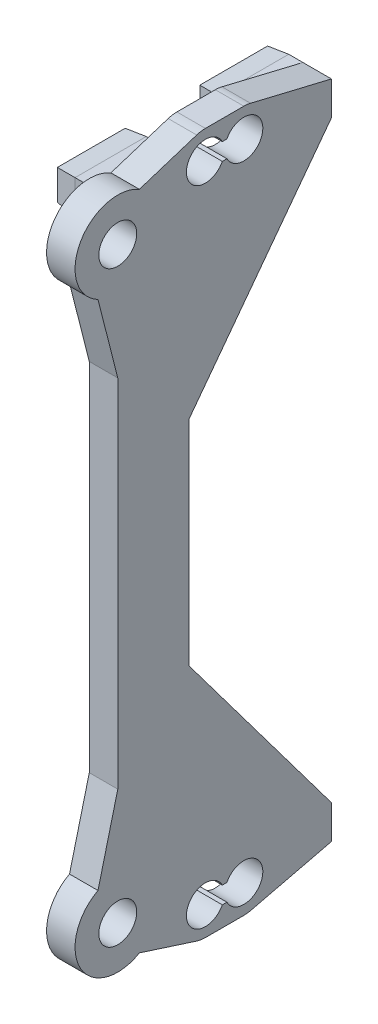
SolidWorks part; units mm, degrees
ref_plane "Front Plane" through (0, 0, 0) normal (0, 0, 1) x (1, 0, 0)
ref_plane "Top Plane" through (0, 0, 0) normal (0, 1, 0) x (1, 0, 0)
ref_plane "Right Plane" through (0, 0, 0) normal (1, 0, 0) x (0, 0, -1)
sketch "SlideGeometry"
  dimension "D1" = 63.5
  dimension "D2" = 12.7
  dimension "D3" = 50.8
  dimension "D4" = 76.2
  dimension "D6" = 12.7
  dimension "D7" = 6.35
  dimension "D8" = 6.35
  dimension "D9" = 12.7
  dimension "D12" = 3.81
  dimension "D5" = 9.525
  dimension "D10" = 12.7
sketch_block_instance "PulleyOutline-1"
sketch_block "PulleyOutline" parameters "D1"=11.1125, "D2"=13.6525
sketch_block_instance "PulleyOutline-2"
sketch_block_instance "PulleyOutline-3"
sketch_block_instance "PulleyOutline-4"
sketch_block_instance "PulleyOutline-5"
sketch_block_instance "PulleyOutline-6"
sketch_block_instance "SlotOutline-1"
sketch_block "SlotOutline" parameters "D1"=6.35, "D2"=3
sketch_block_instance "SlotOutline-3"
sketch "Sketch3" plane through (0, 0, 0) normal (1, 0, 0) x (0, 0, -1)
  circle A0 centre (-3.175, 26.1938) radius 3.81
  circle A1 centre (-3.175, 26.1938) radius 1.5 construction
  dimension "D1" = 7.62
  dimension "D2" = 3
extrude "DowelSupport" add sketch "Sketch3" along normal mid plane 2.54
sketch "Sketch5" plane through (0, 0, 0) normal (1, 0, 0) x (0, 0, -1)
  line L1 (-3.175, -15.875) -> (3.175, -15.875)
  line L2 (-3.175, -15.875) -> (-3.175, 15.875)
  line L3 (-3.175, 15.875) -> (3.175, 15.875)
  line L4 (3.175, -15.875) -> (3.175, 15.875)
  line L5 (-3.175, -15.875) -> (3.175, 15.875) construction
  line L6 (-3.175, 15.875) -> (3.175, -15.875) construction
  point P0 (0, 0)
  dimension "D2" = 31.75
extrude "SliderDowelSupport" add sketch "Sketch5" along normal mid plane 2.54 separate body contours L3 L4 L1 L2
sketch "Sketch8" plane through (0, 0, 0) normal (1, 0, 0) x (0, 0, -1)
  line L0 (4.6355, 28.702) -> (8.0645, 28.702) construction
  line L1 (4.6355, 31.242) -> (8.0645, 31.242)
  line L2 (4.6355, 26.162) -> (8.0645, 26.162)
  line L3 (6.35, 31.75) -> (-6.35, 31.75) construction
  circle A0 centre (4.6355, 28.702) radius 1.5 construction
  circle A1 centre (8.0645, 28.702) radius 1.5 construction
  arc A2 (4.6355, 31.242) -> (4.6355, 26.162) centre (4.6355, 28.702) ccw
  arc A3 (5.7373, 29.7198) -> (5.5245, 28.702) centre (8.0645, 28.702) ccw construction
  arc A4 (8.0645, 31.242) -> (6.35, 30.5761) centre (8.0645, 28.702) ccw construction
  arc A5 (6.35, 30.5761) -> (4.6355, 31.242) centre (4.6355, 28.702) ccw construction
  arc A6 (6.35, 30.5761) -> (5.7373, 29.7198) centre (8.0645, 28.702) ccw construction
  arc A7 (6.9627, 29.7198) -> (6.35, 30.5761) centre (4.6355, 28.702) ccw construction
  arc A8 (7.1755, 28.702) -> (6.9627, 29.7198) centre (4.6355, 28.702) ccw construction
  arc A9 (6.9627, 27.6842) -> (7.1755, 28.702) centre (4.6355, 28.702) ccw construction
  arc A10 (6.35, 26.8279) -> (6.9627, 27.6842) centre (4.6355, 28.702) ccw construction
  arc A11 (5.7373, 27.6842) -> (6.35, 26.8279) centre (8.0645, 28.702) ccw construction
  arc A12 (8.0645, 26.162) -> (8.0645, 31.242) centre (8.0645, 28.702) ccw
  arc A13 (4.6355, 26.162) -> (6.35, 26.8279) centre (4.6355, 28.702) ccw construction
  arc A14 (6.35, 26.8279) -> (8.0645, 26.162) centre (8.0645, 28.702) ccw construction
  arc A15 (5.5245, 28.702) -> (5.7373, 27.6842) centre (8.0645, 28.702) ccw construction
  point P11 (6.35, 28.702)
  dimension "D1" = 3
  dimension "D3" = 5.08
  dimension "D2" = 3.429
  dimension "D4" = 0.508
  dimension "D5" = 9.525
extrude "StringDowelSupport" add sketch "Sketch8" along normal mid plane 2.54 separate body
sketch "Sketch9" plane through (0, 0, 0) normal (1, 0, 0) x (0, 0, -1)
  line B0 (3.175, 26.44) -> (-3.175, 26.44)
  line B1 (3.175, 26.44) -> (3.175, 29.44)
  line B2 (3.175, 29.44) -> (-3.175, 29.44)
  line B3 (-3.175, 26.44) -> (-3.175, 29.44)
  line B4 (3.175, 26.44) -> (-3.175, 29.44) construction
  line B5 (3.175, 29.44) -> (-3.175, 26.44) construction
  line B6 (15.875, 26.44) -> (9.525, 26.44)
  line B7 (15.875, 26.44) -> (15.875, 29.44)
  line B8 (15.875, 29.44) -> (9.525, 29.44)
  line B9 (9.525, 26.44) -> (9.525, 29.44)
sketch_block_instance "3DPTabGeo-1"
sketch_block "3DPTabGeo" parameters "D1"=3, "D2"=6.35
sketch_block_instance "3DPTabGeo-2"
extrude "TabSupport" add sketch "Sketch9" along normal mid plane 2.54
sketch "Sketch10" plane through (0, 0, 0) normal (1, 0, 0) x (0, 0, -1)
  line L0 (-3.175, 15.875) -> (-5.6368, 25.5685)
  line L1 (-5.6368, 25.5685) -> (-0.7132, 26.819) construction
  line L2 (-3.175, 15.875) -> (3.175, 15.875)
  line L3 (3.175, 15.875) -> (3.175, 9.525)
  line L4 (3.175, 9.525) -> (15.875, 26.44)
  line L5 (15.875, 26.44) -> (15.875, 29.44)
  line L6 (15.875, 29.44) -> (8.6571, 31.1719)
  line L7 (8.6571, 31.1719) -> (3.8589, 31.1204)
  line L8 (3.8589, 31.1204) -> (-3.9516, 28.6121)
  line L9 (-3.9516, 28.6121) -> (-2.3984, 23.7754) construction
  line L10 (-5.6368, 25.5685) -> (-3.9516, 28.6121)
  line L11 (3.175, -15.875) -> (3.175, 15.875) construction
  arc A0 (4.6355, 31.242) -> (4.6355, 26.162) centre (4.6355, 28.702) ccw construction
  arc A1 (8.0645, 26.162) -> (8.0645, 31.242) centre (8.0645, 28.702) ccw construction
  point P3 (-3.175, 26.1938)
  dimension "D1" = 5.08
  dimension "D2" = 6.35
extrude "InterSupport" add sketch "Sketch10" along normal mid plane 2.54
sketch "Sketch11" plane through (0, 0, 0) normal (1, 0, 0) x (0, 0, -1)
  line L1 (6.1445, 27.94) -> (6.5555, 27.94)
  line L2 (6.1445, 27.94) -> (6.1445, 29.464) construction
  line L3 (6.1445, 29.464) -> (6.5555, 29.464)
  line L4 (6.5555, 27.94) -> (6.5555, 29.464) construction
  line L5 (6.1445, 27.94) -> (6.5555, 29.464) construction
  line L6 (6.1445, 29.464) -> (6.5555, 27.94) construction
  circle A0 centre (-3.175, 26.1938) radius 1.6905
  arc A1 (6.1445, 29.464) -> (6.1445, 27.94) centre (4.6355, 28.702) ccw
  arc A2 (6.5555, 27.94) -> (6.5555, 29.464) centre (8.0645, 28.702) ccw
  arc A3 (6.323, 28.802) -> (6.1445, 29.464) centre (4.6355, 28.702) ccw construction
  arc A4 (6.5555, 29.464) -> (6.377, 28.802) centre (8.0645, 28.702) ccw construction
  arc A5 (6.377, 28.802) -> (6.377, 28.602) centre (8.0645, 28.702) ccw construction
  arc A6 (6.323, 28.602) -> (6.323, 28.802) centre (4.6355, 28.702) ccw construction
  arc A7 (6.1445, 27.94) -> (6.323, 28.602) centre (4.6355, 28.702) ccw construction
  arc A8 (6.377, 28.602) -> (6.5555, 27.94) centre (8.0645, 28.702) ccw construction
  point P9 (6.35, 28.702)
  dimension "D1" = 3.381
  dimension "D2" = 3.381
  dimension "D3" = 1.524
extrude "DowelHoles" cut sketch "Sketch11" against normal through all both and the other way through all
sketch "Sketch14" plane through (-1.27, 0, 0) normal (-1, 0, 0) x (0, 0, 1)
  line B0 (-9.525, 26.44) -> (-15.875, 26.44)
  line B1 (-9.525, 26.44) -> (-9.525, 29.44)
  line B2 (-9.525, 29.44) -> (-15.875, 29.44)
  line B3 (-15.875, 26.44) -> (-15.875, 29.44)
  line B4 (-9.525, 29.44) -> (-15.875, 26.44) construction
  line B5 (3.175, 26.44) -> (-3.175, 26.44)
  line B6 (3.175, 26.44) -> (3.175, 29.44)
  line B7 (3.175, 29.44) -> (-3.175, 29.44)
  line B8 (-3.175, 26.44) -> (-3.175, 29.44)
sketch_block_instance "3DPTabGeo-3"
sketch_block_instance "3DPTabGeo-4"
extrude "TabBase" add sketch "Sketch14" along normal blind 1.27
sketch "Sketch15" plane through (-2.54, 0, 0) normal (-1, 0, 0) x (0, 0, 1)
  line L0 (-3.175, 29.44) -> (-3.175, 26.44) construction
  line L1 (-3.175, 26.44) -> (3.175, 26.44) construction
  line L2 (3.175, 26.44) -> (3.175, 29.44) construction
  line L3 (3.175, 29.44) -> (-3.175, 29.44) construction
  line L4 (-15.875, 29.44) -> (-15.875, 26.44) construction
  line L5 (-15.875, 26.44) -> (-9.525, 26.44) construction
  line L6 (-9.525, 26.44) -> (-9.525, 29.44) construction
  line L7 (-9.525, 29.44) -> (-15.875, 29.44) construction
  line L8 (-3.175, 29.44) -> (-3.175, 26.44)
  line L9 (-3.175, 26.44) -> (3.175, 26.44)
  line L10 (3.175, 26.44) -> (3.175, 29.44)
  line L11 (3.175, 29.44) -> (-3.175, 29.44)
  line L12 (-15.875, 29.44) -> (-15.875, 26.44)
  line L13 (-15.875, 26.44) -> (-9.525, 26.44)
  line L14 (-9.525, 26.44) -> (-9.525, 29.44)
  line L15 (-9.525, 29.44) -> (-15.875, 29.44)
extrude "TabDraft" add sketch "Sketch15" along normal offset from surface 3 draft 5
mirror "Mirror1" about plane through (0, 0, 0) normal (0, 1, 0) of bodies 118 115
equation "\"StageWidth\"= 2.5in"
equation "\"D1@SlideGeometry\" = \"StageWidth\""
equation "\"StageOffset\"= .5in"
equation "\"D3@SlideGeometry\" = \"StageWidth\" - \"StageOffset\""
equation "\"D4@SlideGeometry\" = \"StageWidth\" + \"StageOffset\""
equation "\"SlideOffset\"= 0.5in"
equation "\"D6@SlideGeometry\" = \"SlideOffset\""
equation "\"D7@SlideGeometry\" = \"StageOffset\" / 2"
equation "\"D8@SlideGeometry\" = \"StageOffset\" / 2"
equation "\"D9@SlideGeometry\" = \"SlideOffset\""
equation "\"OuterThickness\"= 0.1in"
equation "\"D1@SliderDowelSupport\"=\"OuterThickness\""
equation "\"D1@DowelSupport\"=\"OuterThickness\""
equation "\"DowelClearance\"= 3mm + .015in"
equation "\"D1@TabSupport\" = \"OuterThickness\""
equation "\"D1@InterSupport\" = \"OuterThickness\""
equation "\"D1@Sketch11\"=\"DowelClearance\""
equation "\"D2@Sketch11\"=\"DowelClearance\""
equation "\"SliderDowelLength\"= 1"
equation "\"D2@Sketch5\"=\"SliderDowelLength\"+.25in"
